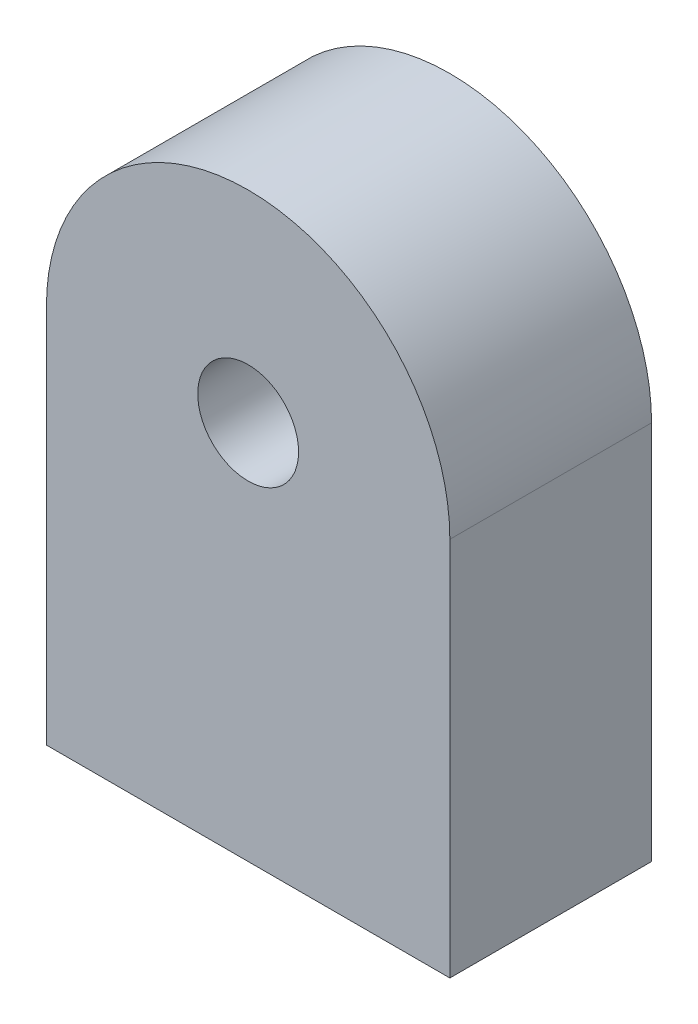
SolidWorks part; units mm, degrees
ref_plane "Front Plane" through (0, 0, 0) normal (0, 0, 1) x (1, 0, 0)
ref_plane "Top Plane" through (0, 0, 0) normal (0, 1, 0) x (1, 0, 0)
ref_plane "Right Plane" through (0, 0, 0) normal (1, 0, 0) x (0, 0, -1)
sketch "Sketch1" plane through (0, 0, 0) normal (0, 0, 1) x (1, 0, 0)
  line L0 (-25.4, 0) -> (-25.4, -47.8423)
  line L1 (-25.4, -47.8423) -> (25.4, -47.8423)
  line L2 (25.4, -47.8423) -> (25.4, 0)
  circle A0 centre (0, 0) radius 6.35
  arc A1 (25.4, 0) -> (-25.4, 0) centre (0, 0) ccw
  dimension "D1" = 12.7
  dimension "D2" = 50.8
extrude "Boss-Extrude1" add sketch "Sketch1" along normal blind 25.4
